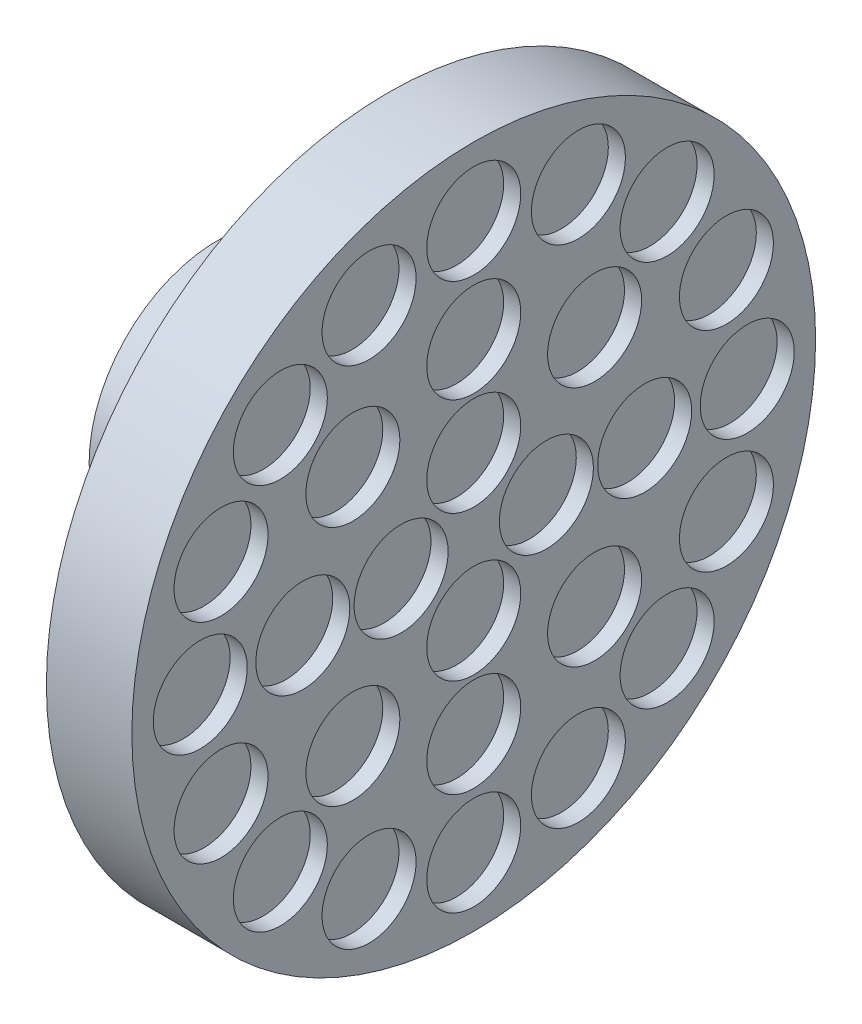
SolidWorks part; units mm, degrees
ref_plane "Plan de face" through (0, 0, 0) normal (1, 0, 0) x (0, 1, 0)
ref_plane "Plan de dessus" through (0, 0, 0) normal (0, 0, 1) x (0, 1, 0)
ref_plane "Plan de droite" through (0, 0, 0) normal (0, 1, 0) x (-1, 0, 0)
sketch "Esquisse1" plane through (0, 0, 0) normal (1, 0, 0) x (0, 1, 0)
  circle A0 centre (0, 0) radius 40
  dimension "D1" = 80
extrude "Boss.-Extru.2" add sketch "Esquisse1" along normal blind 10 contours A0
sketch "Esquisse5" plane through (10, 0, 0) normal (1, 0, 0) x (0, 1, 0)
  circle A0 centre (0, 32) radius 5.5
  circle A1 centre (12.2459, 29.5641) radius 5.5
  circle A2 centre (22.6274, 22.6274) radius 5.5
  circle A3 centre (29.5641, 12.2459) radius 5.5
  circle A4 centre (32, 0) radius 5.5
  circle A5 centre (29.5641, -12.2459) radius 5.5
  circle A6 centre (22.6274, -22.6274) radius 5.5
  circle A7 centre (12.2459, -29.5641) radius 5.5
  circle A8 centre (0, -32) radius 5.5
  circle A9 centre (-12.2459, -29.5641) radius 5.5
  circle A10 centre (-22.6274, -22.6274) radius 5.5
  circle A11 centre (-29.5641, -12.2459) radius 5.5
  circle A12 centre (-32, 0) radius 5.5
  circle A13 centre (-29.5641, 12.2459) radius 5.5
  circle A14 centre (-22.6274, 22.6274) radius 5.5
  circle A15 centre (-12.2459, 29.5641) radius 5.5
  circle A16 centre (0, 20) radius 5.5
  circle A17 centre (14.1421, 14.1421) radius 5.5
  circle A18 centre (20, 0) radius 5.5
  circle A19 centre (14.1421, -14.1421) radius 5.5
  circle A20 centre (0, -20) radius 5.5
  circle A21 centre (-14.1421, -14.1421) radius 5.5
  circle A22 centre (-20, 0) radius 5.5
  circle A23 centre (-14.1421, 14.1421) radius 5.5
  circle A24 centre (0, 8.5) radius 5.5
  circle A25 centre (8.5, 0) radius 5.5
  circle A26 centre (0, -8.5) radius 5.5
  circle A27 centre (-8.5, 0) radius 5.5
  point P35 (0, 0)
  point P52 (0, 0)
  point P62 (0, 0)
  dimension "D1" = 11
  dimension "D4" = 11
  dimension "D7" = 11
  dimension "D2" = 32
  dimension "D5" = 20
  dimension "D8" = 8.5
  dimension "D3" = 16
  dimension "D6" = 8
  dimension "D9" = 4
extrude "Enlèv. mat.-Extru.2" cut sketch "Esquisse5" against normal blind 2
sketch "Esquisse6" plane through (0, 0, 0) normal (-1, 0, 0) x (0, -1, 0)
  circle A0 centre (0, 0) radius 15
  dimension "D1" = 30
extrude "Boss.-Extru.3" add sketch "Esquisse6" along normal blind 20
fillet "Congé1" radius 10 1 edges at (0, 0, 15)
sketch "Esquisse7" plane through (-20, 0, 0) normal (-1, 0, 0) x (0, 0, 1)
  circle A0 centre (0, 0) radius 5
  dimension "D1" = 10
extrude "Enlèv. mat.-Extru.3" cut sketch "Esquisse7" against normal blind 16
